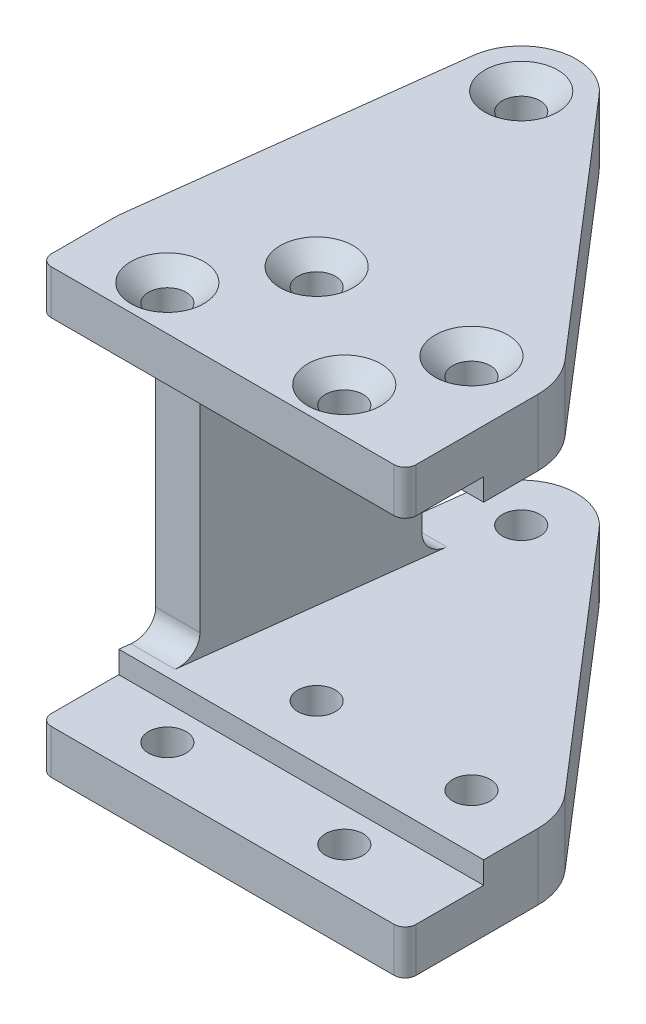
SolidWorks part; units mm, degrees
ref_plane "前视基准面" through (0, 0, 0) normal (0, 0, 1) x (1, 0, 0)
ref_plane "上视基准面" through (0, 0, 0) normal (0, 1, 0) x (1, 0, 0)
ref_plane "右视基准面" through (0, 0, 0) normal (1, 0, 0) x (0, 0, -1)
other "Configuration Table"
sketch "草图1" plane through (0, 0, 0) normal (0, 1, 0) x (1, 0, 0)
  line L0 (0, 48.1766) -> (0, -11.3107) construction
  line L1 (-28.6592, 0) -> (28.3272, 0) construction
  line L2 (-15.5, -4) -> (15.5, -4)
  line L6 (-15.5, -4) -> (-15.5, 3)
  line L10 (-11.9622, 31.6135) -> (-15.5, 3)
  line L11 (-3.2123, 34.264) -> (16.0452, 11.9168)
  line L12 (15.5, -4) -> (17.5, -4)
  line L13 (17.5, -4) -> (17.5, 8)
  circle A0 centre (-8, 0) radius 1.7
  circle A1 centre (8, 0) radius 1.7
  arc A2 (-3.2123, 34.264) -> (-11.9622, 31.6135) centre (-7, 31) ccw
  circle A6 centre (-7, 31) radius 1.7
  arc A11 (17.5, 8) -> (16.0452, 11.9168) centre (11.5, 8) ccw
  circle A12 centre (11.5, 8) radius 1.7
  circle A13 centre (-2.5, 8) radius 1.7
  point P14 (0, -4)
  dimension "D1" = 3.4
  dimension "D3" = 4
  dimension "D6" = 10
  dimension "D7" = 2
  dimension "D8" = 3.4
  dimension "D9" = 8
  dimension "D10" = 6
  dimension "D11" = 3.4
  dimension "D12" = 3.4
  dimension "D13" = 14
  dimension "D15" = 4.5
  dimension "D14" = 23
  dimension "D2" = 8
  dimension "D4" = 31
  dimension "D5" = 7
extrude "凸台-拉伸1" add sketch "草图1" along normal blind 6
sketch "草图3" plane through (0, 0, 0) normal (0, -1, 0) x (1, 0, 0)
  line L1 (-15.5, 4) -> (17.5, 4) construction
  line L5 (-13.3474, -15) -> (-3.5403, -15) construction
  line L11 (-11.9622, -31.6135) -> (-15.5, -3) construction
  line L12 (-15.1207, -6.068) -> (-12.912, -23.932)
  line L13 (-12.912, -23.932) -> (-8.912, -23.932)
  line L14 (-8.912, -23.932) -> (-11.1207, -6.068)
  line L15 (-11.1207, -6.068) -> (-15.1207, -6.068)
  dimension "D1" = 4
  dimension "D2" = 18
  dimension "D3" = 12
extrude "凸台-拉伸3" add sketch "草图3" along normal blind 14
fillet "圆角1" radius 1 2 edges at (-15.5, 3, 4) (17.5, 3, 4)
fillet "圆角2" radius 10 1 edges at (-15.5, 3, -3)
sketch "草图12" plane through (0, 6, 0) normal (0, 1, 0) x (1, 0, 0)
  point P0 (-2.5, 8)
  point P3 (11.5, 8)
  point P6 (8, 0)
  point P9 (-8, 0)
  point P12 (-7, 31)
hole_wizard "M3 十字槽半沉头木螺钉的锥形沉头孔1" positions "草图12" profile "草图13" countersink size "M3" standard "GB" end condition up to next
sketch "草图13" plane through (-2.5, 6, -8) normal (1, 0, 0) x (0, 0, 1)
  line L0 (0, 0) -> (0, 20)
  line L1 (0, 20) -> (1.7, 20)
  line L2 (1.7, 20) -> (1.7, 1.6)
  line L3 (1.7, 1.6) -> (3.3, 0)
  line L5 (3.3, 0) -> (0, 0)
  line L6 (-1.7, 1.6) -> (-3.3, 0) construction
  line L11 (0, -6.35) -> (0, 107.95) construction
  dimension "通孔孔直径" = 3.4
  dimension "通孔孔深度" = 20
  dimension "近端锥形沉头孔直径" = 6.6
  dimension "近端锥形沉头孔角度" = 90
mirror "镜向1" about plane through (0, -14, 0) normal (0, -1, 0) of bodies 123 109
sketch "草图14" plane through (17.5, 0, 0) normal (1, 0, 0) x (0, 0, -1)
  line L0 (6.068, -14) -> (-4.4, -14) construction
  line L1 (6.068, -28) -> (6.068, 0) construction
  line L2 (-4, -28) -> (-4, -34) construction
  line L3 (-11.9, -30) -> (3.1, -30)
  line L4 (-11.9, -30) -> (-11.9, 2)
  line L5 (-11.9, 2) -> (3.1, 2)
  line L6 (3.1, -30) -> (3.1, 2)
  line L7 (-11.9, -30) -> (3.1, 2) construction
  line L8 (-11.9, 2) -> (3.1, -30) construction
  dimension "D1" = 7.1
  dimension "D2" = 15
  dimension "D3" = 32
extrude "切除-拉伸3" cut sketch "草图14" against normal through all
fillet "圆角3" radius 2 4 edges at (-10.912, -28, -23.932) (-13.1207, -28, -6.068) (-13.1207, 0, -6.068) (-10.912, 0, -23.932)
